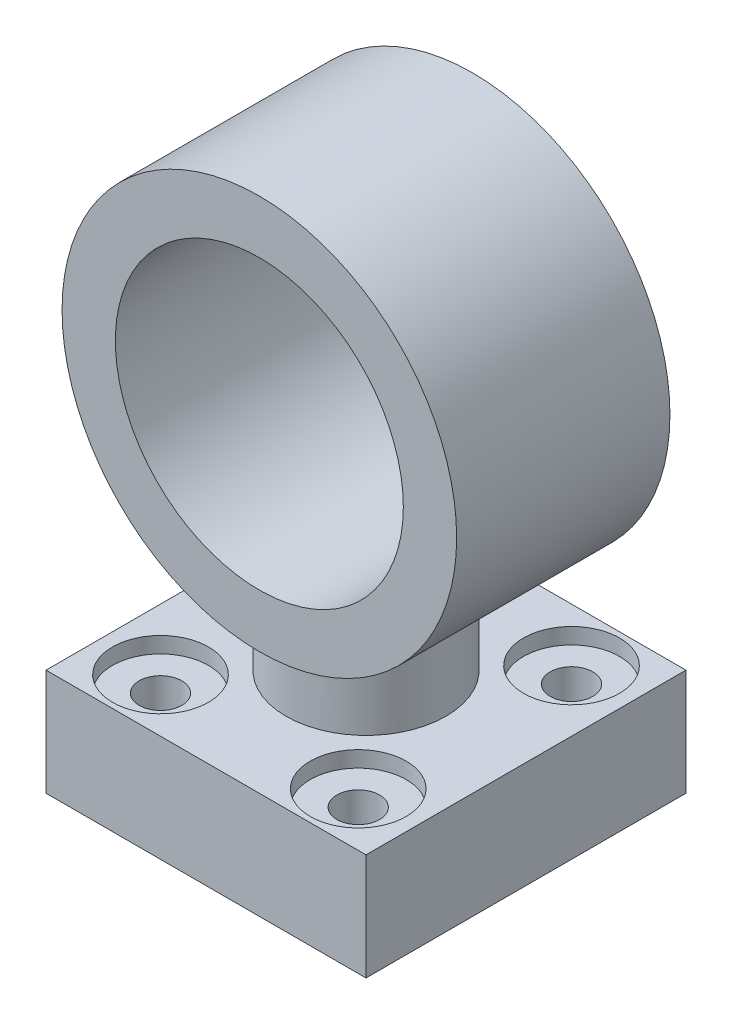
SolidWorks part; units mm, degrees
ref_plane "前视基准面" through (0, 0, 0) normal (0, 0, 1) x (1, 0, 0)
ref_plane "上视基准面" through (0, 0, 0) normal (0, 1, 0) x (1, 0, 0)
ref_plane "右视基准面" through (0, 0, 0) normal (1, 0, 0) x (0, 0, -1)
sketch "草图1" plane through (0, 0, 0) normal (0, 0, 1) x (1, 0, 0)
  circle A0 centre (0, 0) radius 18.5
  circle A1 centre (0, 0) radius 13.5
  dimension "D1" = 27
  dimension "D2" = 37
extrude "凸台-拉伸1" add sketch "草图1" along normal mid plane 20
ref_plane "基准面1" through (0, -25, 0) normal (0, 1, 0) x (1, 0, 0)
sketch "草图2" plane through (0, -25, 0) normal (0, 1, 0) x (1, 0, 0)
  circle A0 centre (0, 0) radius 7.5
  dimension "D1" = 15
extrude "凸台-拉伸2" add sketch "草图2" along normal up to surface (6.5 mm away)
sketch "草图3" plane through (0, -25, 0) normal (0, -1, 0) x (1, 0, 0)
  line L1 (-15, 15) -> (15, 15)
  line L2 (-15, 15) -> (-15, -15)
  line L3 (-15, -15) -> (15, -15)
  line L4 (15, 15) -> (15, -15)
  line L5 (0, -15) -> (0, 15) construction
  line L6 (-15, 0) -> (15, 0) construction
  point P0 (0, 0)
  dimension "D1" = 30
  dimension "D2" = 30
extrude "凸台-拉伸3" add sketch "草图3" along normal blind 10
sketch "草图4" plane through (0, -35, 0) normal (0, -1, 0) x (1, 0, 0)
  line L1 (-9.2704, 10) -> (9.2704, 10) construction
  line L2 (-9.2704, 10) -> (-9.2704, -10) construction
  line L3 (-9.2704, -10) -> (9.2704, -10) construction
  line L4 (9.2704, 10) -> (9.2704, -10) construction
  line L5 (0, -10) -> (0, 10) construction
  line L6 (-9.2704, 0) -> (9.2704, 0) construction
  circle A0 centre (-9.2704, 10) radius 2
  circle A1 centre (9.2704, 10) radius 2
  circle A2 centre (-9.2704, -10) radius 2
  circle A3 centre (9.2704, -10) radius 2
  point P0 (0, 0)
  dimension "D2" = 4
  dimension "D1" = 20
extrude "切除-拉伸1" cut sketch "草图4" against normal blind 15
sketch "草图5" plane through (0, -25, 0) normal (0, 1, 0) x (1, 0, 0)
  line L1 (9.2704, 10) -> (-9.2704, 10) construction
  line L2 (9.2704, 10) -> (9.2704, -10) construction
  line L3 (9.2704, -10) -> (-9.2704, -10) construction
  line L4 (-9.2704, 10) -> (-9.2704, -10) construction
  line L5 (0, -10) -> (0, 10) construction
  line L6 (9.2704, 0) -> (-9.2704, 0) construction
  circle A0 centre (-9.2704, -10) radius 4.5
  circle A1 centre (9.2704, -10) radius 4.5
  circle A2 centre (9.2704, 10) radius 4.5
  circle A3 centre (-9.2704, 10) radius 4.5
  point P3 (0, 0)
  dimension "D1" = 9
extrude "切除-拉伸2" cut sketch "草图5" against normal blind 1.5
